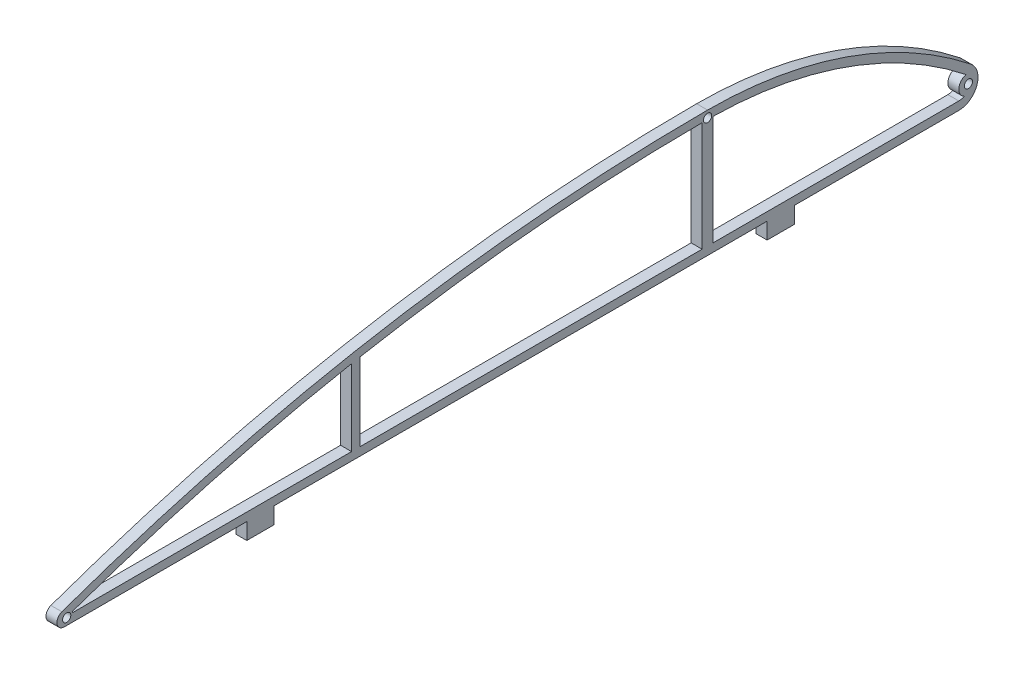
SolidWorks part; units mm, degrees
other "Marquage1"
sketch "Esquisse8" plane through (8, 0, -172.8424) normal (1, 0, 0) x (0, 0, -1)
other "Marquage2"
sketch "Esquisse10" plane through (-6, 20, -172.8424) normal (-0.8365, 0.2588, -0.483) x (-0.5, 0, 0.866)
other "Marquage3"
sketch "Esquisse11" plane through (0, 0, 0) normal (-0.0501, -0.1345, 0.9896) x (0.9942, 0.0873, 0.0622)
ref_plane "Plan de face" through (0, 0, 0) normal (0, 0, 1) x (1, 0, 0)
ref_plane "Plan de dessus" through (0, 0, 0) normal (0, 1, 0) x (1, 0, 0)
ref_plane "Plan de droite" through (0, 0, 0) normal (1, 0, 0) x (0, 0, -1)
sketch "Esquisse2" plane through (0, 0, 0) normal (1, 0, 0) x (0, 0, -1)
  line L0 (0, 0) -> (170.8732, 0)
  arc A1 (173.0499, 6.2408) -> (125, 23) centre (125, -54.2609) ccw
  arc A3 (170.8732, 0) -> (173.0499, 6.2408) centre (170.8732, 3.5) ccw
  arc A4 (125, 23) -> (0, 0) centre (125, -328.1739) ccw
  point P10 (180, 0)
  dimension "D1" = 180
  dimension "D2" = 3.5
  dimension "D3" = 23
  dimension "D4" = 55
extrude "Boss.-Extru.1" add sketch "Esquisse2" along normal blind 2
sketch "Esquisse4" plane through (2, 0, 0) normal (1, 0, 0) x (0, 0, -1)
  line L0 (125, 23) -> (125, 21.75) construction
  line L1 (0, 0) -> (8, 1.25) construction
  line L10 (174.369, 3.3283) -> (172.619, 3.3283) construction
  circle A6 centre (125, 21.75) radius 0.75
  circle A12 centre (172.619, 3.3283) radius 0.75
  arc A13 (170.8732, 0) -> (173.0499, 6.2408) centre (170.8732, 3.5) ccw construction
  circle A15 centre (8, 1.25) radius 0.75
  dimension "D1" = 1.5
  dimension "D2" = 1.5
  dimension "D7" = 1.5
  dimension "D3" = 1.25
  dimension "D4" = 8
  dimension "D5" = 1.25
  dimension "D6" = 1.75
extrude "Enlèv. mat.-Extru.2" cut sketch "Esquisse4" against normal through all
sketch "Esquisse9" plane through (0, 0, 0) normal (1, 0, 0) x (0, 0, -1)
  line L26 (126, 1.5) -> (170.8732, 1.5)
  line L35 (8.4369, 1.5) -> (170.8732, 1.5)
  line L36 (9.0712, 1.5) -> (60, 1.5)
  line L37 (124, 21.4417) -> (124, 1.5)
  line L39 (126, 21.4417) -> (126, 1.5)
  line L40 (61.5, 1.5) -> (124, 1.5)
  line L42 (60, 1.5) -> (60, 15.4055)
  line L44 (61.5, 1.5) -> (61.5, 15.6859)
  arc A12 (172.1725, 5.0204) -> (172.117, 5.0662) centre (170.8732, 3.5) ccw
  arc A18 (126, 21.4417) -> (126.022, 21.4931) centre (125, 21.9) ccw
  arc A20 (60, 15.4055) -> (9.0038, 1.6999) centre (125, -328.1739) ccw
  circle A30 centre (125, 21.9) radius 1.1
  arc A35 (170.8732, 1.5) -> (172.117, 5.0662) centre (170.8732, 3.5) ccw
  arc A39 (172.117, 5.0662) -> (125, 21.5) centre (125, -54.2609) ccw
  arc A40 (125, 21.5) -> (8.4369, 1.5) centre (125, -328.1739) ccw
  arc A41 (170.8732, 1.5) -> (171.8515, 1.7556) centre (170.8732, 3.5) ccw
  arc A42 (172.117, 5.0662) -> (126.022, 21.4931) centre (125, -54.2609) ccw
  arc A43 (123.9759, 21.4985) -> (61.5, 15.6859) centre (125, -328.1739) ccw
  arc A44 (123.9759, 21.4985) -> (124, 21.4417) centre (125, 21.9) ccw
  circle A46 centre (172.619, 3.3283) radius 1.75
  arc A49 (172.1725, 5.0204) -> (171.8515, 1.7556) centre (172.619, 3.3283) ccw
  circle A53 centre (8, 1.25) radius 1.1
  arc A54 (9.0712, 1.5) -> (9.0038, 1.6999) centre (8, 1.25) ccw
  dimension "D1" = 1.5
  dimension "D2" = 0.5
  dimension "D3" = 0.5
  dimension "D5" = 2
  dimension "D4" = 0.5
  dimension "D6" = 1.5
  dimension "D7" = 60
extrude "Enlèv. mat.-Extru.3" cut sketch "Esquisse9" along normal blind 4
fillet "Congé2" radius 1.35 1 edges at (1, 0, 0)
sketch "Esquisse12" plane through (0, 0, 0) normal (0, -1, 0) x (1, 0, 0)
  line L0 (0, -140.8732) -> (2, -140.8732)
  line L1 (0, -7.5659) -> (0, -170.8732) construction
  line L2 (2, -7.5659) -> (2, -170.8732) construction
  line L3 (2, -170.8732) -> (0, -170.8732) construction
  line L4 (0, -135.8732) -> (2, -135.8732)
  line L5 (0, -45.8732) -> (2, -45.8732)
  line L6 (0, -40.8732) -> (2, -40.8732)
  point P14 (0, 0)
  line M5 (2, -170.8732) -> (2, -7.5659)
  line M7 (0, -7.5659) -> (0, -170.8732)
  dimension "D1" = 30
  dimension "D2" = 5
  dimension "D3" = 90
  dimension "D4" = 5
extrude "Boss.-Extru.2" add sketch "Esquisse12" along normal blind 3 contours L4 L0 M7 M5 | L6 L5 M7 M5
